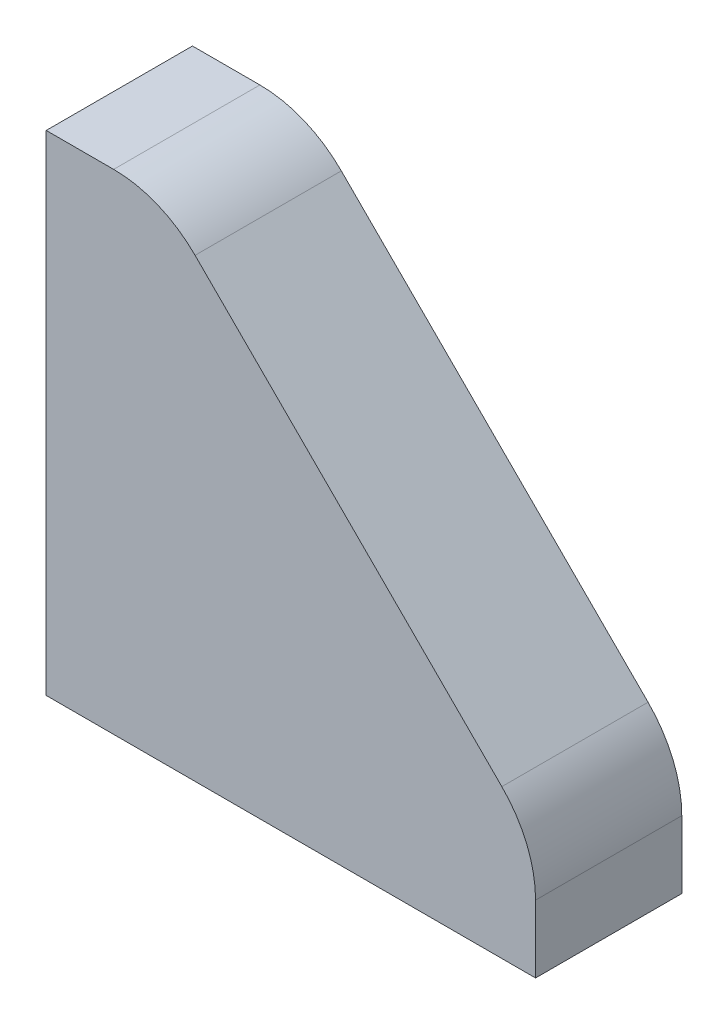
SolidWorks part; units mm, degrees
material "Low Carbon Steel"
ref_plane "Front Plane" through (0, 0, 0) normal (0, 0, 1) x (1, 0, 0)
ref_plane "Top Plane" through (0, 0, 0) normal (0, 1, 0) x (1, 0, 0)
ref_plane "Right Plane" through (0, 0, 0) normal (1, 0, 0) x (0, 0, -1)
sketch "Sketch1" plane through (0, 0, 0) normal (0, 0, 1) x (1, 0, 0)
  line L0 (0, 0) -> (85, 0)
  line L1 (85, 0) -> (85, 20)
  line L2 (85, 20) -> (20, 85)
  line L3 (20, 85) -> (0, 85)
  line L4 (0, 85) -> (0, 0)
  dimension "D1" = 85
  dimension "D2" = 20
extrude "Boss-Extrude1" add sketch "Sketch1" along normal mid plane 25.4 contours L2 L3 L4 L0 L1
fillet "Fillet1" radius 20 2 edges at (85, 20, 0) (20, 85, 0)
other "Freeze***"
